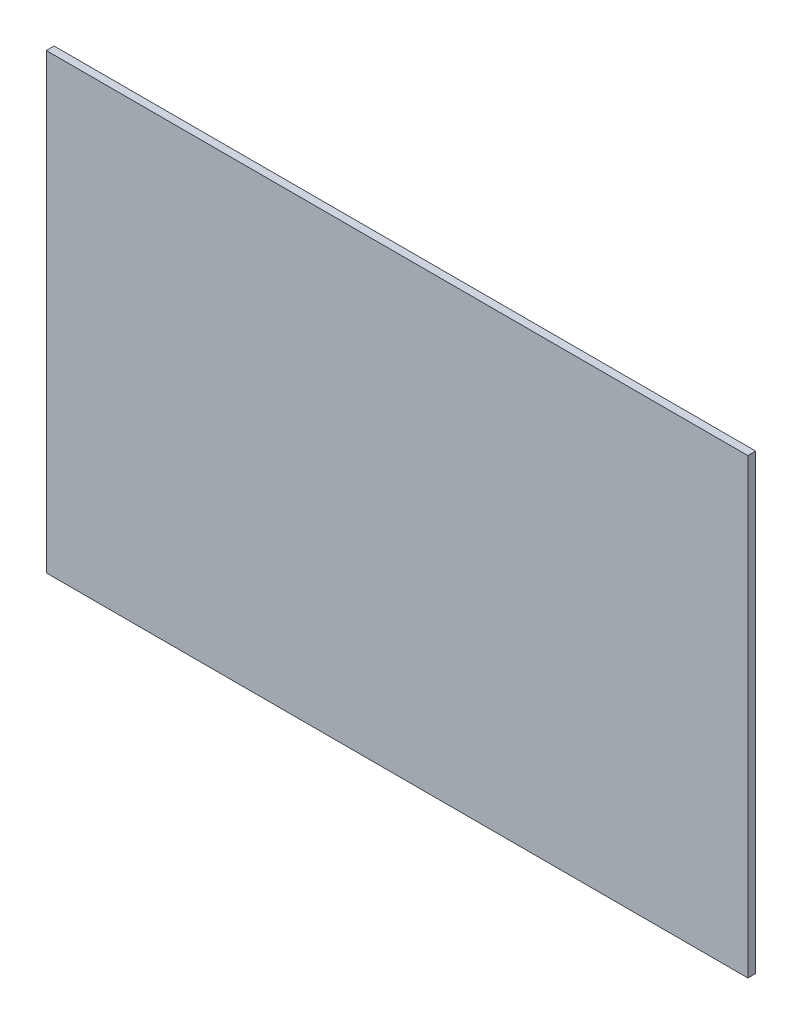
SolidWorks part; units mm, degrees
material "Клен"
ref_plane "Спереди" through (0, 0, 0) normal (0, 0, 1) x (1, 0, 0)
ref_plane "Сверху" through (0, 0, 0) normal (0, 1, 0) x (1, 0, 0)
ref_plane "Справа" through (0, 0, 0) normal (1, 0, 0) x (0, 0, -1)
sketch "Эскиз1" plane through (0, 0, 0) normal (0, 0, 1) x (1, 0, 0)
  line L0 (-367.4727, 191.9298) -> (170.5273, 191.9298)
  line L1 (-367.4727, 191.9298) -> (-367.4727, -154.9702)
  line L2 (-367.4727, -154.9702) -> (170.5273, -154.9702)
  line L3 (170.5273, 191.9298) -> (170.5273, -154.9702)
extrude "Бобышка-Вытянуть1" add sketch "Эскиз1" along normal blind 6
